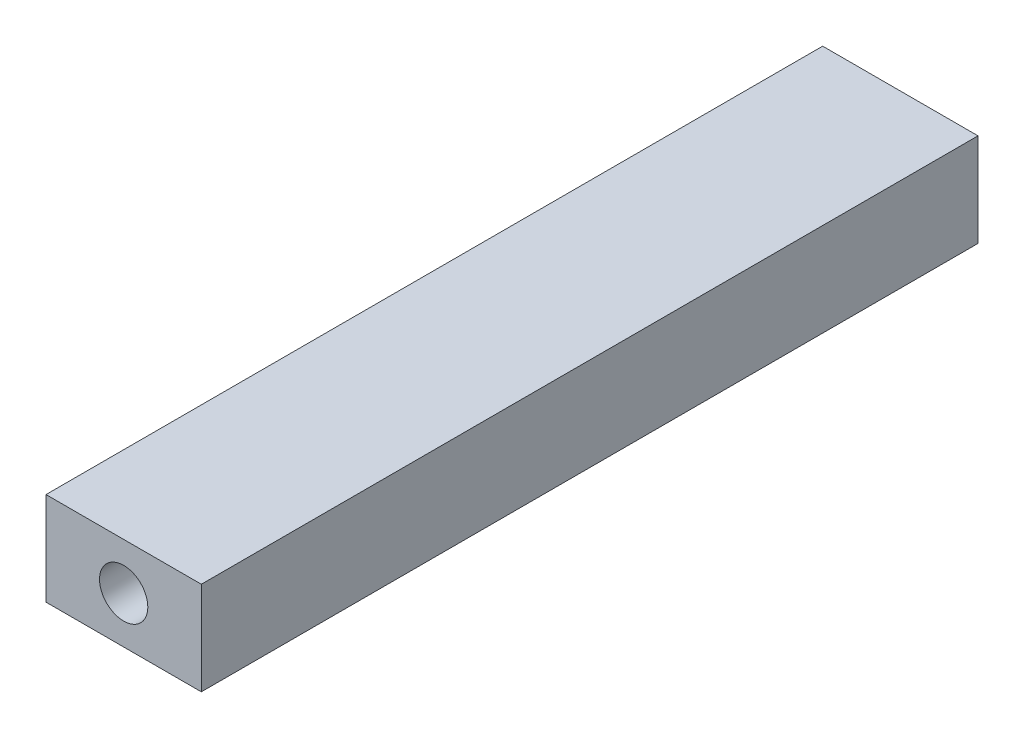
SolidWorks part; units mm, degrees
ref_plane "Front Plane" through (0, 0, 0) normal (0, 0, 1) x (1, 0, 0)
ref_plane "Top Plane" through (0, 0, 0) normal (0, 1, 0) x (1, 0, 0)
ref_plane "Right Plane" through (0, 0, 0) normal (1, 0, 0) x (0, 0, -1)
sketch "Sketch3" plane through (0, 0, 0) normal (0, 0, 1) x (1, 0, 0)
  line L0 (0, 0) -> (100, 60) construction
  line L1 (0, 0) -> (100, 0)
  line L2 (0, 0) -> (0, 60)
  line L3 (0, 60) -> (100, 60)
  line L4 (100, 0) -> (100, 60)
  circle A0 centre (50, 30) radius 15.5456
  point P7 (0, 0)
  point P8 (50, 30)
  dimension "D1" = 100
  dimension "D2" = 60
extrude "Boss-Extrude3" add sketch "Sketch3" along normal blind 500
